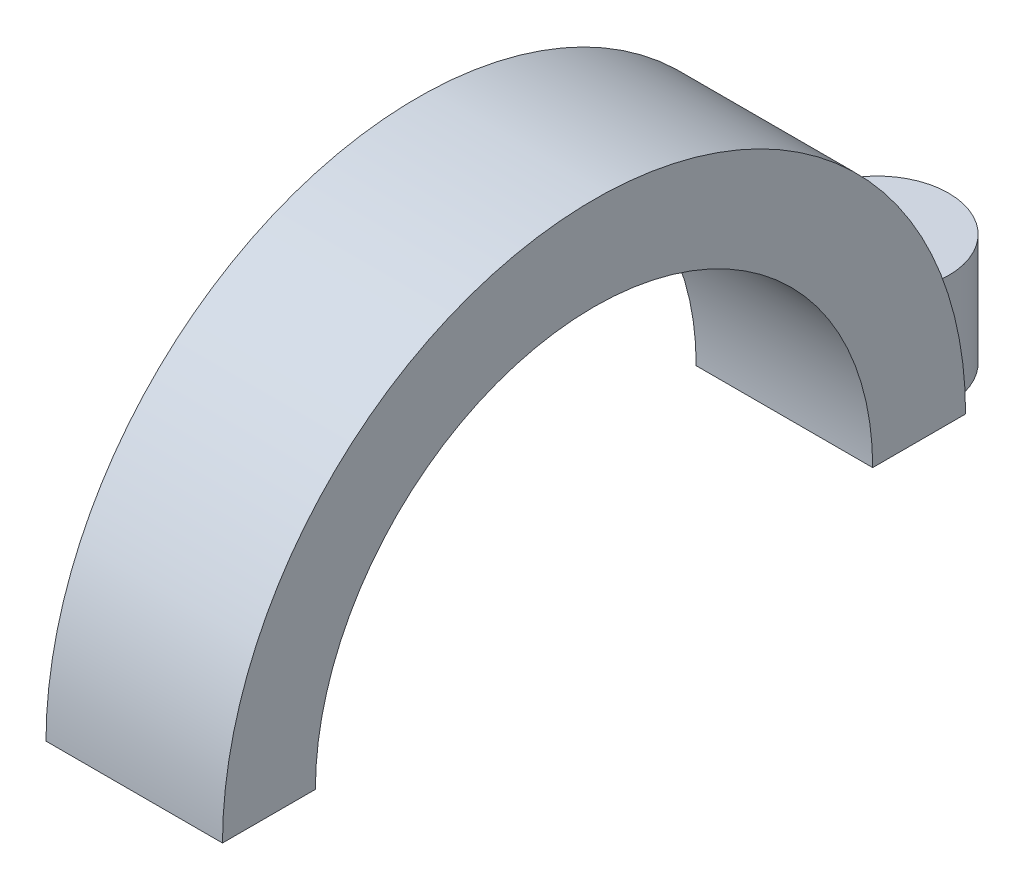
SolidWorks part; units mm, degrees
ref_plane "Front Plane" through (0, 0, 0) normal (0, 0, 1) x (1, 0, 0)
ref_plane "Top Plane" through (0, 0, 0) normal (0, 1, 0) x (1, 0, 0)
ref_plane "Right Plane" through (0, 0, 0) normal (1, 0, 0) x (0, 0, -1)
sketch "Sketch1" plane through (0, 0, 0) normal (1, 0, 0) x (0, 0, -1)
  line L0 (-508, 0) -> (508, 0)
  arc A0 (381, 0) -> (-381, 0) centre (0, 0) ccw
  arc A1 (508, 0) -> (-508, 0) centre (0, 0) ccw
  circle A2 centre (0, 0) radius 508 construction
  circle A3 centre (0, 0) radius 381 construction
  dimension "D2" = 762
  dimension "D1" = 127
extrude "Boss-Extrude1" add sketch "Sketch1" along normal mid plane 241.3 contours L0 A1 A0
sketch "Sketch2" plane through (0, 0, 0) normal (0, -1, 0) x (1, 0, 0)
  line L0 (120.65, -508) -> (-120.65, -508) construction
  circle A0 centre (0, -508) radius 97.5
  dimension "D1" = 195
extrude "Boss-Extrude2" add sketch "Sketch2" against normal blind 152.5
